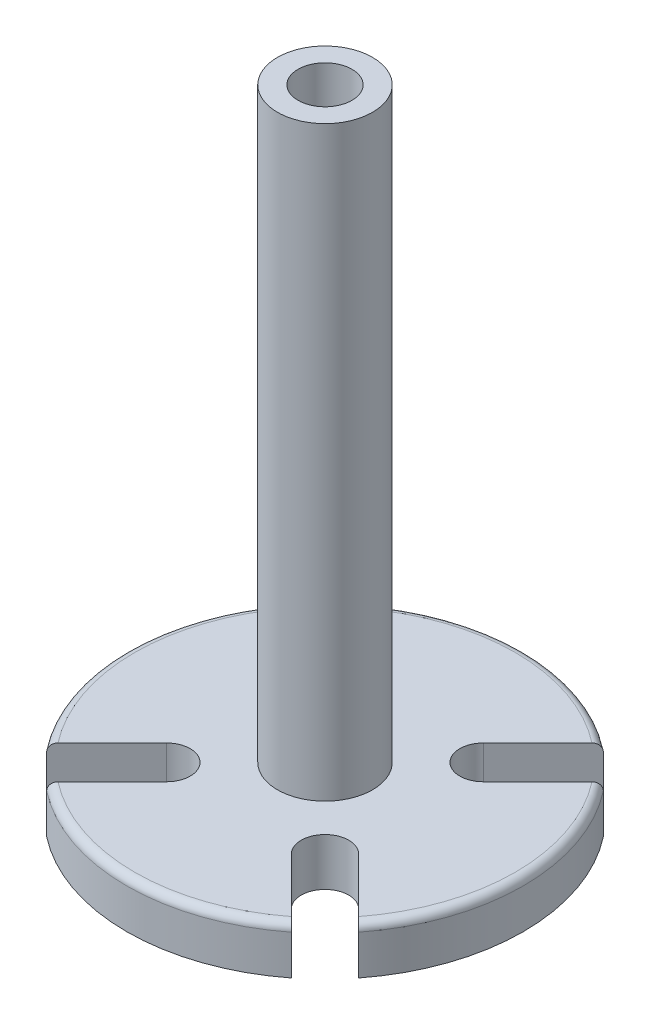
SolidWorks part; units mm, degrees
ref_plane "前视基准面" through (0, 0, 0) normal (0, 0, 1) x (1, 0, 0)
ref_plane "上视基准面" through (0, 0, 0) normal (0, 1, 0) x (1, 0, 0)
ref_plane "右视基准面" through (0, 0, 0) normal (1, 0, 0) x (0, 0, -1)
sketch "草图1" plane through (0, 0, 0) normal (0, 0, 1) x (1, 0, 0)
  line L0 (0, 0) -> (0, 80)
  line L1 (0, 80) -> (-6, 80)
  line L2 (-6, 80) -> (-6, 6)
  line L3 (-6, 6) -> (-25, 6)
  line L4 (-25, 6) -> (-25, 0)
  line L5 (-25, 0) -> (0, 0)
  dimension "D1" = 80
  dimension "D2" = 6
  dimension "D3" = 25
  dimension "D4" = 6
revolve "旋转1" add sketch "草图1" angle 360 about L0
fillet "圆角1" radius 1 1 edges at (0, 6, -25)
hole_wizard "M8 螺纹槽口的螺纹槽口钻头1" positions "草图2" profile "草图4" size "M8" standard "GB" slot yes
sketch "草图2" plane through (0, 80, 0) normal (0, 1, 0) x (1, 0, 0)
  point P0 (0, 0)
sketch "草图4" plane through (0, 80, 0) normal (1, 0, 0) x (0, 0, 1)
  line L0 (0, 0) -> (0, 22.0429)
  line L1 (0, 22.0429) -> (3.4, 20)
  line L2 (3.4, 20) -> (3.4, 0)
  line L5 (3.4, 0) -> (0, 0)
  line L10 (0, 22.0429) -> (-3.4, 20) construction
  line L11 (0, -6.35) -> (0, 107.95) construction
  dimension "孔直径" = 6.8
  dimension "孔深度" = 20
  dimension "导头角度" = 118
sketch "草图5" plane through (0, 6, 0) normal (0, 1, 0) x (1, 0, 0)
  line L0 (10, -10) -> (20.6066, -20.6066) construction
  line L1 (-10, -10) -> (10, -10) construction
  line L2 (-10, -10) -> (-10, 10) construction
  line L3 (-10, 10) -> (10, 10) construction
  line L4 (10, -10) -> (10, 10) construction
  line L5 (-10, -10) -> (10, 10) construction
  line L6 (-10, 10) -> (10, -10) construction
  line L7 (12.1213, -7.8787) -> (22.7279, -18.4853)
  line L8 (7.8787, -12.1213) -> (18.4853, -22.7279)
  line L9 (-10, -10) -> (-20.6066, -20.6066) construction
  line L10 (-7.8787, -12.1213) -> (-18.4853, -22.7279)
  line L11 (-12.1213, -7.8787) -> (-22.7279, -18.4853)
  line L12 (-10, 10) -> (-20.6066, 20.6066) construction
  line L13 (-12.1213, 7.8787) -> (-22.7279, 18.4853)
  line L14 (-7.8787, 12.1213) -> (-18.4853, 22.7279)
  line L15 (10, 10) -> (20.6066, 20.6066) construction
  line L16 (7.8787, 12.1213) -> (18.4853, 22.7279)
  line L17 (12.1213, 7.8787) -> (22.7279, 18.4853)
  arc A4 (12.1213, -7.8787) -> (7.8787, -12.1213) centre (10, -10) ccw
  arc A5 (18.4853, -22.7279) -> (22.7279, -18.4853) centre (20.6066, -20.6066) ccw
  arc A6 (-7.8787, -12.1213) -> (-12.1213, -7.8787) centre (-10, -10) ccw
  arc A7 (-22.7279, -18.4853) -> (-18.4853, -22.7279) centre (-20.6066, -20.6066) ccw
  arc A8 (-12.1213, 7.8787) -> (-7.8787, 12.1213) centre (-10, 10) ccw
  arc A9 (-18.4853, 22.7279) -> (-22.7279, 18.4853) centre (-20.6066, 20.6066) ccw
  arc A10 (7.8787, 12.1213) -> (12.1213, 7.8787) centre (10, 10) ccw
  arc A11 (22.7279, 18.4853) -> (18.4853, 22.7279) centre (20.6066, 20.6066) ccw
  point P0 (0, 0)
  point P6 (15.3033, -15.3033)
  point P15 (0, 0)
  point P17 (-15.3033, -15.3033)
  point P23 (0, 0)
  point P25 (-15.3033, 15.3033)
  point P31 (0, 0)
  point P33 (15.3033, 15.3033)
  point P39 (0, 0)
  dimension "D3" = 3
  dimension "D1" = 20
  dimension "D2" = 20
  dimension "D4" = 15
  dimension "D5" = 4
extrude "切除-拉伸1" cut sketch "草图5" against normal through all
